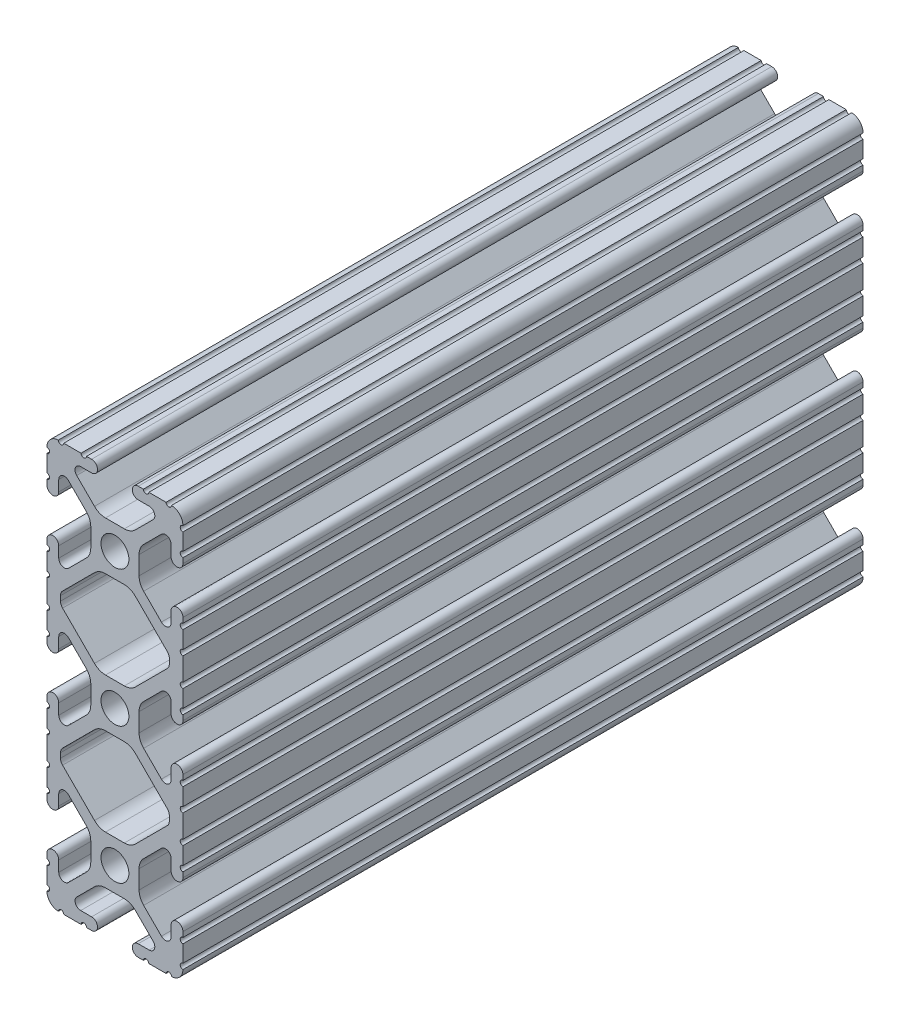
SolidWorks part; units mm, degrees
ref_plane "Front Plane" through (0, 0, 0) normal (0, 0, 1) x (1, 0, 0)
ref_plane "Top Plane" through (0, 0, 0) normal (0, 1, 0) x (1, 0, 0)
ref_plane "Right Plane" through (0, 0, 0) normal (1, 0, 0) x (0, 0, -1)
sketch "Sketch1" plane through (0, 0, 0) normal (0, 0, 1) x (1, 0, 0)
  line L0 (-12.7, 0) -> (12.7, 0) construction
  line L1 (-10.16, 13.1469) -> (-10.16, 12.2531)
  line L2 (-3.8143, 20.0397) -> (-9.7731, 14.0808)
  line L3 (0, 20.8915) -> (-1.7578, 20.8915)
  line L7 (-1.7578, 4.5085) -> (0, 4.5085)
  line L8 (-9.7731, 11.3192) -> (-3.8143, 5.3603)
  line L9 (-6.3246, 38.1) -> (-9.5504, 38.1)
  line L10 (-12.7, 34.8742) -> (-12.7, 31.7246)
  line L11 (-12.7, 30.7086) -> (-12.7, 29.7561)
  line L12 (-10.4902, 29.7561) -> (-10.4902, 31.7602)
  line L13 (-8.6864, 32.5073) -> (-5.3603, 29.1812)
  line L14 (-4.5085, 27.1248) -> (-4.5085, 23.6752)
  line L15 (-5.3603, 21.6188) -> (-8.6864, 18.2927)
  line L16 (-10.4902, 19.0398) -> (-10.4902, 21.0439)
  line L17 (-12.7, 21.0439) -> (-12.7, 20.0914)
  line L18 (-12.7, 19.0754) -> (-12.7, 15.8496)
  line L19 (-12.7, 14.8336) -> (-12.7, 10.5664)
  line L20 (-12.7, 9.5504) -> (-12.7, 6.3246)
  line L21 (-12.7, 5.3086) -> (-12.7, 4.3561)
  line L22 (-10.4902, 4.3561) -> (-10.4902, 6.3602)
  line L23 (-8.6864, 7.1073) -> (-5.3603, 3.7812)
  line L24 (-4.5085, 1.7248) -> (-4.5085, 0)
  line L25 (-11.5951, 28.6512) -> (-11.5951, 22.1488) construction
  line L26 (-11.5951, 25.4) -> (0, 25.4) construction
  line L27 (-12.7, 31.7246) -> (-6.3246, 38.1) construction
  line L28 (-12.7, 12.7) -> (0, 12.7) construction
  line L29 (-9.4336, 32.8168) -> (0, 32.8168) construction
  line L30 (-9.4336, 17.9832) -> (0, 17.9832) construction
  line L31 (-9.4336, 32.8168) -> (-9.4336, 17.9832) construction
  line L44 (0, 29.9085) -> (-1.7578, 29.9085)
  line L45 (-3.8143, 30.7603) -> (-7.1404, 34.0864)
  line L46 (-6.3932, 35.8902) -> (-4.3561, 35.8902)
  line L47 (-4.3561, 38.1) -> (-5.3086, 38.1)
  line L48 (0, 0) -> (0, 38.1) construction
  arc A0 (0, 28.0035) -> (0, 22.7965) centre (0, 25.4) ccw
  arc A1 (0, 2.6035) -> (-2.6035, 0) centre (0, 0) ccw
  arc A2 (-9.7731, 14.0808) -> (-10.16, 13.1469) centre (-8.8392, 13.1469) ccw
  arc A3 (-1.7578, 20.8915) -> (-3.8143, 20.0397) centre (-1.7578, 17.9832) ccw
  arc A8 (-3.8143, 5.3603) -> (-1.7578, 4.5085) centre (-1.7578, 7.4168) ccw
  arc A9 (-10.16, 12.2531) -> (-9.7731, 11.3192) centre (-8.8392, 12.2531) ccw
  arc A10 (-6.3246, 38.1) -> (-5.3086, 38.1) centre (-5.8166, 38.1) ccw
  arc A11 (-10.5664, 38.1) -> (-9.5504, 38.1) centre (-10.0584, 38.1) ccw
  arc A12 (-10.5664, 38.1) -> (-12.7, 35.8902) centre (-10.4888, 35.8902) ccw
  arc A13 (-12.7, 34.8742) -> (-12.7, 35.8902) centre (-12.7, 35.3822) ccw
  arc A14 (-12.7, 30.7086) -> (-12.7, 31.7246) centre (-12.7, 31.2166) ccw
  arc A15 (-12.7, 29.7561) -> (-10.4902, 29.7561) centre (-11.5951, 29.7561) ccw
  arc A16 (-8.6864, 32.5073) -> (-10.4902, 31.7602) centre (-9.4336, 31.7602) ccw
  arc A17 (-4.5085, 27.1248) -> (-5.3603, 29.1812) centre (-7.4168, 27.1248) ccw
  arc A18 (-5.3603, 21.6188) -> (-4.5085, 23.6752) centre (-7.4168, 23.6752) ccw
  arc A19 (-10.4902, 19.0398) -> (-8.6864, 18.2927) centre (-9.4336, 19.0398) ccw
  arc A20 (-10.4902, 21.0439) -> (-12.7, 21.0439) centre (-11.5951, 21.0439) ccw
  arc A21 (-12.7, 19.0754) -> (-12.7, 20.0914) centre (-12.7, 19.5834) ccw
  arc A22 (-12.7, 14.8336) -> (-12.7, 15.8496) centre (-12.7, 15.3416) ccw
  arc A23 (-12.7, 9.5504) -> (-12.7, 10.5664) centre (-12.7, 10.0584) ccw
  arc A24 (-12.7, 5.3086) -> (-12.7, 6.3246) centre (-12.7, 5.8166) ccw
  arc A25 (-12.7, 4.3561) -> (-10.4902, 4.3561) centre (-11.5951, 4.3561) ccw
  arc A26 (-8.6864, 7.1073) -> (-10.4902, 6.3602) centre (-9.4336, 6.3602) ccw
  arc A27 (-4.5085, 1.7248) -> (-5.3603, 3.7812) centre (-7.4168, 1.7248) ccw
  arc A49 (-3.8143, 30.7603) -> (-1.7578, 29.9085) centre (-1.7578, 32.8168) ccw
  arc A50 (-6.3932, 35.8902) -> (-7.1404, 34.0864) centre (-6.3932, 34.8336) ccw
  arc A51 (-4.3561, 35.8902) -> (-4.3561, 38.1) centre (-4.3561, 36.9951) ccw
  point P53 (-9.4336, 25.4)
  point P63 (-0.8789, 20.8915)
  dimension "D16" = 0.508
  dimension "D19" = 2.6035
  dimension "D27" = 1.0566
  dimension "D28" = 1.3208
  dimension "Rail Height" = 76.2
  dimension "Rail Width" = 25.4
  dimension "D3" = 2.2098
  dimension "D4" = 2.2098
  dimension "D5" = 2.2098
  dimension "D6" = 25.4
  dimension "D7" = 9.017
  dimension "D8" = 9.017
  dimension "TSlot Width" = 6.5024
  dimension "D9" = 2.2098
  dimension "D10" = 9.017
  dimension "D11" = 9.017
  dimension "D12" = 6.5024
  dimension "D13" = 6.5024
  dimension "D14" = 10.5664
  dimension "D15" = 5.3086
  dimension "D17" = 2.2098
  dimension "D18" = 16.383
  dimension "D2" = 45
  dimension "D20" = 45
  dimension "D21" = 45
  dimension "D22" = 2.54
  dimension "D23" = 25.4
  dimension "D24" = 4.2672
  dimension "D25" = 12.7508
  dimension "D26" = 14.8336
sketch "Sketch2" plane through (0, 0, 0) normal (1, 0, 0) x (0, 0, -1)
  line L0 (-1524, 0) -> (1524, 0)
  point P2 (-1460.5, 0)
  point P3 (1460.5, 0)
  dimension "Length" = 3048
  dimension "D1" = 63.5
  dimension "D2" = 63.5
sketch "Sketch3" plane through (0, 0, 0) normal (0, 0, 1) x (1, 0, 0)
  line L0 (-4.5085, 1.7248) -> (-4.5085, 0) construction
  line L1 (-8.6864, 7.1073) -> (-5.3603, 3.7812) construction
  line L2 (-10.4902, 4.3561) -> (-10.4902, 6.3602) construction
  line L3 (-12.7, 5.3086) -> (-12.7, 4.3561) construction
  line L4 (-12.7, 9.5504) -> (-12.7, 6.3246) construction
  line L5 (-12.7, 14.8336) -> (-12.7, 10.5664) construction
  line L6 (-12.7, 19.0754) -> (-12.7, 15.8496) construction
  line L7 (-12.7, 21.0439) -> (-12.7, 20.0914) construction
  line L8 (-10.4902, 19.0398) -> (-10.4902, 21.0439) construction
  line L9 (-5.3603, 21.6188) -> (-8.6864, 18.2927) construction
  line L10 (-4.5085, 27.1248) -> (-4.5085, 23.6752) construction
  line L11 (-8.6864, 32.5073) -> (-5.3603, 29.1812) construction
  line L12 (-10.4902, 29.7561) -> (-10.4902, 31.7602) construction
  line L13 (-12.7, 30.7086) -> (-12.7, 29.7561) construction
  line L14 (-12.7, 34.8742) -> (-12.7, 31.7246) construction
  line L15 (-6.3246, 38.1) -> (-9.5504, 38.1) construction
  line L16 (-4.3561, 38.1) -> (-5.3086, 38.1) construction
  line L17 (-6.3932, 35.8902) -> (-4.3561, 35.8902) construction
  line L18 (-3.8143, 30.7603) -> (-7.1404, 34.0864) construction
  line L19 (0, 29.9085) -> (-1.7578, 29.9085) construction
  line L20 (-1.7578, 4.5085) -> (0, 4.5085) construction
  line L21 (-9.7731, 11.3192) -> (-3.8143, 5.3603) construction
  line L22 (-10.16, 13.1469) -> (-10.16, 12.2531) construction
  line L23 (-3.8143, 20.0397) -> (-9.7731, 14.0808) construction
  line L24 (0, 20.8915) -> (-1.7578, 20.8915) construction
  line L25 (-4.5085, 1.7248) -> (-4.5085, 0)
  line L26 (-8.6864, 7.1073) -> (-5.3603, 3.7812)
  line L27 (-10.4902, 4.3561) -> (-10.4902, 6.3602)
  line L28 (-12.7, 5.3086) -> (-12.7, 4.3561)
  line L29 (-12.7, 9.5504) -> (-12.7, 6.3246)
  line L30 (-12.7, 14.8336) -> (-12.7, 10.5664)
  line L31 (-12.7, 19.0754) -> (-12.7, 15.8496)
  line L32 (-12.7, 21.0439) -> (-12.7, 20.0914)
  line L33 (-10.4902, 19.0398) -> (-10.4902, 21.0439)
  line L34 (-5.3603, 21.6188) -> (-8.6864, 18.2927)
  line L35 (-4.5085, 27.1248) -> (-4.5085, 23.6752)
  line L36 (-8.6864, 32.5073) -> (-5.3603, 29.1812)
  line L37 (-10.4902, 29.7561) -> (-10.4902, 31.7602)
  line L38 (-12.7, 30.7086) -> (-12.7, 29.7561)
  line L39 (-12.7, 34.8742) -> (-12.7, 31.7246)
  line L40 (-6.3246, 38.1) -> (-9.5504, 38.1)
  line L41 (-4.3561, 38.1) -> (-5.3086, 38.1)
  line L42 (-6.3932, 35.8902) -> (-4.3561, 35.8902)
  line L43 (-3.8143, 30.7603) -> (-7.1404, 34.0864)
  line L44 (0, 29.9085) -> (-1.7578, 29.9085)
  line L45 (-1.7578, 4.5085) -> (0, 4.5085)
  line L46 (-9.7731, 11.3192) -> (-3.8143, 5.3603)
  line L47 (-10.16, 13.1469) -> (-10.16, 12.2531)
  line L48 (-3.8143, 20.0397) -> (-9.7731, 14.0808)
  line L49 (0, 20.8915) -> (-1.7578, 20.8915)
  line L50 (0, 29.9085) -> (0, 28.0035)
  line L51 (0, 22.7965) -> (0, 20.8915)
  line L52 (0, 4.5085) -> (0, 2.6035)
  line L53 (-4.5085, 0) -> (-2.6035, 0)
  arc A0 (-4.5085, 1.7248) -> (-5.3603, 3.7812) centre (-7.4168, 1.7248) ccw construction
  arc A1 (-8.6864, 7.1073) -> (-10.4902, 6.3602) centre (-9.4336, 6.3602) ccw construction
  arc A2 (-12.7, 4.3561) -> (-10.4902, 4.3561) centre (-11.5951, 4.3561) ccw construction
  arc A3 (-12.7, 5.3086) -> (-12.7, 6.3246) centre (-12.7, 5.8166) ccw construction
  arc A4 (-12.7, 9.5504) -> (-12.7, 10.5664) centre (-12.7, 10.0584) ccw construction
  arc A5 (-12.7, 14.8336) -> (-12.7, 15.8496) centre (-12.7, 15.3416) ccw construction
  arc A6 (-12.7, 19.0754) -> (-12.7, 20.0914) centre (-12.7, 19.5834) ccw construction
  arc A7 (-10.4902, 21.0439) -> (-12.7, 21.0439) centre (-11.5951, 21.0439) ccw construction
  arc A8 (-10.4902, 19.0398) -> (-8.6864, 18.2927) centre (-9.4336, 19.0398) ccw construction
  arc A9 (-5.3603, 21.6188) -> (-4.5085, 23.6752) centre (-7.4168, 23.6752) ccw construction
  arc A10 (-4.5085, 27.1248) -> (-5.3603, 29.1812) centre (-7.4168, 27.1248) ccw construction
  arc A11 (-8.6864, 32.5073) -> (-10.4902, 31.7602) centre (-9.4336, 31.7602) ccw construction
  arc A12 (-12.7, 29.7561) -> (-10.4902, 29.7561) centre (-11.5951, 29.7561) ccw construction
  arc A13 (-12.7, 30.7086) -> (-12.7, 31.7246) centre (-12.7, 31.2166) ccw construction
  arc A14 (-12.7, 34.8742) -> (-12.7, 35.8902) centre (-12.7, 35.3822) ccw construction
  arc A15 (-10.5664, 38.1) -> (-12.7, 35.8902) centre (-10.4888, 35.8902) ccw construction
  arc A16 (-10.5664, 38.1) -> (-9.5504, 38.1) centre (-10.0584, 38.1) ccw construction
  arc A17 (-6.3246, 38.1) -> (-5.3086, 38.1) centre (-5.8166, 38.1) ccw construction
  arc A18 (-4.3561, 35.8902) -> (-4.3561, 38.1) centre (-4.3561, 36.9951) ccw construction
  arc A19 (-6.3932, 35.8902) -> (-7.1404, 34.0864) centre (-6.3932, 34.8336) ccw construction
  arc A20 (-3.8143, 30.7603) -> (-1.7578, 29.9085) centre (-1.7578, 32.8168) ccw construction
  arc A21 (-3.8143, 5.3603) -> (-1.7578, 4.5085) centre (-1.7578, 7.4168) ccw construction
  arc A22 (-10.16, 12.2531) -> (-9.7731, 11.3192) centre (-8.8392, 12.2531) ccw construction
  arc A23 (-9.7731, 14.0808) -> (-10.16, 13.1469) centre (-8.8392, 13.1469) ccw construction
  arc A24 (-1.7578, 20.8915) -> (-3.8143, 20.0397) centre (-1.7578, 17.9832) ccw construction
  arc A25 (0, 2.6035) -> (-2.6035, 0) centre (0, 0) ccw construction
  arc A26 (0, 28.0035) -> (0, 22.7965) centre (0, 25.4) ccw construction
  arc A27 (-4.5085, 1.7248) -> (-5.3603, 3.7812) centre (-7.4168, 1.7248) ccw
  arc A28 (-8.6864, 7.1073) -> (-10.4902, 6.3602) centre (-9.4336, 6.3602) ccw
  arc A29 (-12.7, 4.3561) -> (-10.4902, 4.3561) centre (-11.5951, 4.3561) ccw
  arc A30 (-12.7, 5.3086) -> (-12.7, 6.3246) centre (-12.7, 5.8166) ccw
  arc A31 (-12.7, 9.5504) -> (-12.7, 10.5664) centre (-12.7, 10.0584) ccw
  arc A32 (-12.7, 14.8336) -> (-12.7, 15.8496) centre (-12.7, 15.3416) ccw
  arc A33 (-12.7, 19.0754) -> (-12.7, 20.0914) centre (-12.7, 19.5834) ccw
  arc A34 (-10.4902, 21.0439) -> (-12.7, 21.0439) centre (-11.5951, 21.0439) ccw
  arc A35 (-10.4902, 19.0398) -> (-8.6864, 18.2927) centre (-9.4336, 19.0398) ccw
  arc A36 (-5.3603, 21.6188) -> (-4.5085, 23.6752) centre (-7.4168, 23.6752) ccw
  arc A37 (-4.5085, 27.1248) -> (-5.3603, 29.1812) centre (-7.4168, 27.1248) ccw
  arc A38 (-8.6864, 32.5073) -> (-10.4902, 31.7602) centre (-9.4336, 31.7602) ccw
  arc A39 (-12.7, 29.7561) -> (-10.4902, 29.7561) centre (-11.5951, 29.7561) ccw
  arc A40 (-12.7, 30.7086) -> (-12.7, 31.7246) centre (-12.7, 31.2166) ccw
  arc A41 (-12.7, 34.8742) -> (-12.7, 35.8902) centre (-12.7, 35.3822) ccw
  arc A42 (-10.5664, 38.1) -> (-12.7, 35.8902) centre (-10.4888, 35.8902) ccw
  arc A43 (-10.5664, 38.1) -> (-9.5504, 38.1) centre (-10.0584, 38.1) ccw
  arc A44 (-6.3246, 38.1) -> (-5.3086, 38.1) centre (-5.8166, 38.1) ccw
  arc A45 (-4.3561, 35.8902) -> (-4.3561, 38.1) centre (-4.3561, 36.9951) ccw
  arc A46 (-6.3932, 35.8902) -> (-7.1404, 34.0864) centre (-6.3932, 34.8336) ccw
  arc A47 (-3.8143, 30.7603) -> (-1.7578, 29.9085) centre (-1.7578, 32.8168) ccw
  arc A48 (-3.8143, 5.3603) -> (-1.7578, 4.5085) centre (-1.7578, 7.4168) ccw
  arc A49 (-10.16, 12.2531) -> (-9.7731, 11.3192) centre (-8.8392, 12.2531) ccw
  arc A50 (-9.7731, 14.0808) -> (-10.16, 13.1469) centre (-8.8392, 13.1469) ccw
  arc A51 (-1.7578, 20.8915) -> (-3.8143, 20.0397) centre (-1.7578, 17.9832) ccw
  arc A52 (0, 2.6035) -> (-2.6035, 0) centre (0, 0) ccw
  arc A53 (0, 28.0035) -> (0, 22.7965) centre (0, 25.4) ccw
extrude "Boss-Extrude1" add sketch "Sketch3" along normal mid plane 3048
mirror "Mirror1" about plane through (0, 0, 0) normal (1, 0, 0) of bodies 104
mirror "Mirror2" about plane through (0, 0, 0) normal (0, 1, 0) of bodies 105
sketch "Sketch4" plane through (0, 0, 1524) normal (0, 0, 1) x (1, 0, 0)
  line L1 (-12.7, 38.1) -> (12.7985, 38.1)
  line L2 (-12.7, 38.1) -> (-12.7, -38.2441)
  line L3 (-12.7, -38.2441) -> (12.7985, -38.2441)
  line L4 (12.7985, 38.1) -> (12.7985, -38.2441)
extrude "Cut-Extrude1" cut sketch "Sketch4" against normal blind 2921
equation "\"D3@Sketch1\" = \"Rail Width@Sketch1\" * 0.0870in"
equation "\"D4@Sketch1\"=\"D3@Sketch1\""
equation "\"D5@Sketch1\"=\"D3@Sketch1\""
equation "\"D6@Sketch1\" = \"Rail Width@Sketch1\""
equation "\"D7@Sketch1\" = \"Rail Width@Sketch1\" * 0.3550in"
equation "\"D8@Sketch1\"=\"D7@Sketch1\""
equation "\"D9@Sketch1\"=\"D4@Sketch1\""
equation "\"D10@Sketch1\"=\"D8@Sketch1\""
equation "\"D11@Sketch1\"=\"D7@Sketch1\""
equation "\"D12@Sketch1\"=\"TSlot Width@Sketch1\""
equation "\"D14@Sketch1\" = \"Rail Width@Sketch1\" * 0.4160in"
equation "\"D15@Sketch1\" = \"Rail Width@Sketch1\" * 0.2090in"
equation "\"D16@Sketch1\" = \"Rail Width@Sketch1\" * 0.0200in"
equation "\"D17@Sketch1\"=\"D9@Sketch1\""
equation "\"D18@Sketch1\" = \"Rail Width@Sketch1\" * 0.6450in"
equation "\"D19@Sketch1\" = \"Rail Width@Sketch1\" * 0.1025in"
equation "\"D22@Sketch1\"=\"Rail Width@Sketch1\"*0.10"
equation "\"D23@Sketch1\"=\"Rail Width@Sketch1\""
equation "\"D24@Sketch1\"=\"Rail Width@Sketch1\"*0.1680in"
equation "\"D25@Sketch1\"=\"Rail Width@Sketch1\"*0.5020in"
equation "\"D26@Sketch1\"=\"Rail Width@Sketch1\"*0.584"
equation "\"D27@Sketch1\"=\"Rail Width@Sketch1\"*0.0416in"
equation "\"D28@Sketch1\"=\"Rail Width@Sketch1\"*0.052"
equation "\"D1@Boss-Extrude1\" = \"Length@Sketch2\""
equation "\"D2@Sketch2\"=\"D1@Sketch2\""
equation "\"D13@Sketch1\"=\"TSlot Width@Sketch1\""
